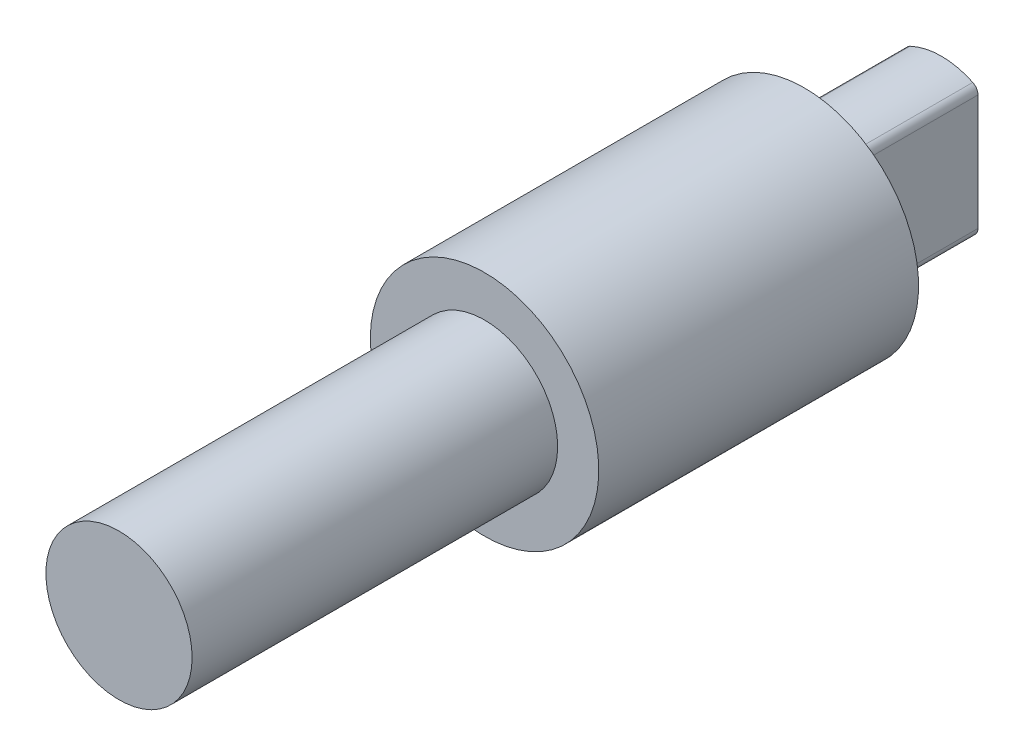
SolidWorks part; units mm, degrees
ref_plane "Front Plane" through (0, 0, 0) normal (0, 0, 1) x (1, 0, 0)
ref_plane "Top Plane" through (0, 0, 0) normal (0, 1, 0) x (1, 0, 0)
ref_plane "Right Plane" through (0, 0, 0) normal (1, 0, 0) x (0, 0, -1)
sketch "Sketch2" plane through (0, 0, 0) normal (0, 1, 0) x (1, 0, 0)
  line L1 (0, -40) -> (8, -40)
  line L3 (8, 40) -> (0, 40)
  line L4 (0, -40) -> (0, 40) construction
  line L7 (8, 25) -> (8, 40)
  line L8 (12.5, 25) -> (8, 25)
  line L9 (-20, 0) -> (12.5, 0) construction
  line L10 (12.5, -10) -> (8, -10)
  line L11 (8, -10) -> (8, -40)
  line L14 (0, 364.1003) -> (0, -285.8462) construction
  line L15 (0, -40) -> (0, 40)
  line L16 (12.5, 25) -> (12.5, -10)
  dimension "D5" = 0
  dimension "D1" = 8
  dimension "D2" = 80
  dimension "D4" = 12.5
  dimension "D6" = 30
  dimension "D7" = 8
  dimension "D3" = 15
revolve "Revolve2" add sketch "Sketch2" angle 360 about L14
sketch "Sketch4" plane through (0, 0, 40) normal (0, 0, 1) x (1, 0, 0)
  line L1 (-6.61, 1.39) -> (-7.8783, 1.39)
  line L2 (-6.61, 1.39) -> (-6.61, -1.39)
  line L3 (-6.61, -1.39) -> (-7.8783, -1.39)
  arc A1 (-7.8783, 1.39) -> (-7.8783, -1.39) centre (0, 0) ccw
  circle A2 centre (0, 0) radius 8 construction
  point P7 (-8, 0)
  dimension "D1" = 2.78
  dimension "D2" = 1.39
extrude "Cut-Extrude2" cut sketch "Sketch4" against normal blind 30
sketch "Sketch6" plane through (0, 0, 40) normal (0, 0, 1) x (1, 0, 0)
  circle A0 centre (0, 0) radius 8
  circle A1 centre (0, 0) radius 8 construction
extrude "Boss-Extrude1" add sketch "Sketch6" along normal blind 10
sketch "Sketch7" plane through (0, 0, -40) normal (0, 0, -1) x (-1, 0, 0)
  line L0 (-4, 6.9282) -> (-4, -6.9282)
  line L1 (4, 6.9282) -> (4, -6.9282)
  line L2 (4, 6.9282) -> (-4, -6.9282) construction
  arc A0 (-4, 6.9282) -> (-4, -6.9282) centre (0, 0) ccw
  circle A1 centre (0, 0) radius 8 construction
  arc A2 (4, -6.9282) -> (4, 6.9282) centre (0, 0) ccw
  dimension "D1" = 8
extrude "Cut-Extrude3" cut sketch "Sketch7" against normal up to surface (15 mm away) up to face at (-8, 0, -25)
fillet "Fillet1" radius 1 4 edges at (4, -6.9282, -32.5) (4, 6.9282, -32.5) (-4, 6.9282, -32.5) (-4, -6.9282, -32.5)
sketch "Sketch8" plane through (-4, 0, 0) normal (-1, 0, 0) x (0, 0, 1)
  line L0 (-40, 6.3246) -> (-40, -6.3246) construction
  line L1 (-40, -6.3246) -> (-25, 6.3246) construction
  line L2 (-25, 6.3246) -> (-25, -6.3246) construction
  circle A0 centre (-32.5, 0) radius 2.5
  dimension "D1" = 5
  dimension "D2" = 7.5
extrude "Cut-Extrude4" cut sketch "Sketch8" against normal blind 1
equation "\"shaft inner diameter\"= 15mm "
equation "\"keyway_height\" = 1.39mm "
equation "\"D1@Sketch2\"=\"primary shaft small diameter\"/2"
equation "\"D1@Sketch4\"=\"keyway_width\""
equation "\"keyway_length\" = 30mm "
equation "\"D1@Cut-Extrude2\"=\"keyway_length\""
equation "\"steering column length\" = 555mm "
equation "\"horizontal shaft length\" = 90mm "
equation "\"pinion width\" = 26.5mm "
equation "\"D1@Boss-Extrude1\"=\"short_bearing_outer_width\""
equation "\"shaft outer diameter\"= 20mm "
equation "\"keyway_width\" = 2.78mm "
equation "\"u_joint clearance\" = 30mm "
equation "\"u_joint thickness\" = 7.5mm "
equation "\"short_bearing_outer_width\" = 10mm "
equation "\"number of teeth\" = 18mm "
equation "\"D2@Sketch2\"=\"horizontal shaft length\"-\"short_bearing_outer_width\""
equation "\"D4@Sketch2\"=\"secondary shaft large diameter\"/2"
equation "\"D6@Sketch2\"=\"keyway_length\""
equation "\"D7@Sketch2\"=\"secondary shaft small diameter\"/2"
equation "\"column angle\" = 45deg "
equation "\"steering wheel bolt width\" = 6mm "
equation "\"steering wheel bolt length\" = 40mm "
equation "\"bushing length\" = 40mm "
equation "\"bushing thickness\" = 3mm "
equation "\"column bushing diameter\" = \"primary shaft small diameter\" + 4 "
equation "\"column bushing distance\" = \"steering column length\"/4 "
equation "\"D2@Sketch4\"=\"keyway_height\""
equation "\"wheel base\" = 1561mm "
equation "\"track\" = 1354mm "
equation "\"turning radius\" = 2000mm "
equation "\"steering arm length\" = 100mm "
equation "\"turn to lock\" = 0.75mm "
equation "\"pin hole diameter\" = 10mm "
equation "\"rack hole to hole\" = 500mm "
equation "\"rack length\" = \"rack hole to hole\" + \"pin hole diameter\"*2 "
equation "\"rack height\"= \"pin hole diameter\" * 2mm"
equation "\"max turning angle\" = atn(\"wheel base\" / (\"turning radius\" - 0.5 * \"track\")) "
equation "\"max travel\" = 2 * \"steering arm length\" * sin(0.5 * \"max turning angle\") "
equation "\"pitch diameter\" = \"max travel\"/(pi * \"turn to lock\") "
equation "\"module\" = \"pitch diameter\" / \"number of teeth\" "
equation "\"pressure angle\" = 20deg "
equation "\"tie rod length\" = 305mm "
equation "\"tie rod diameter\"= 10mm"
equation "\"D1@Sketch7\"=\"primary shaft small diameter\"/2"
equation "\"primary shaft small diameter\" = 16mm "
equation "\"primary shaft large diameter\" = 24mm "
equation "\"secondary shaft small diameter\" = 16mm "
equation "\"secondary shaft large diameter\" = 25mm "
equation "\"tie rod inner diameter\" = 6.6mm "
equation "\"tie rod outer diameter\" = 8.1mm "
